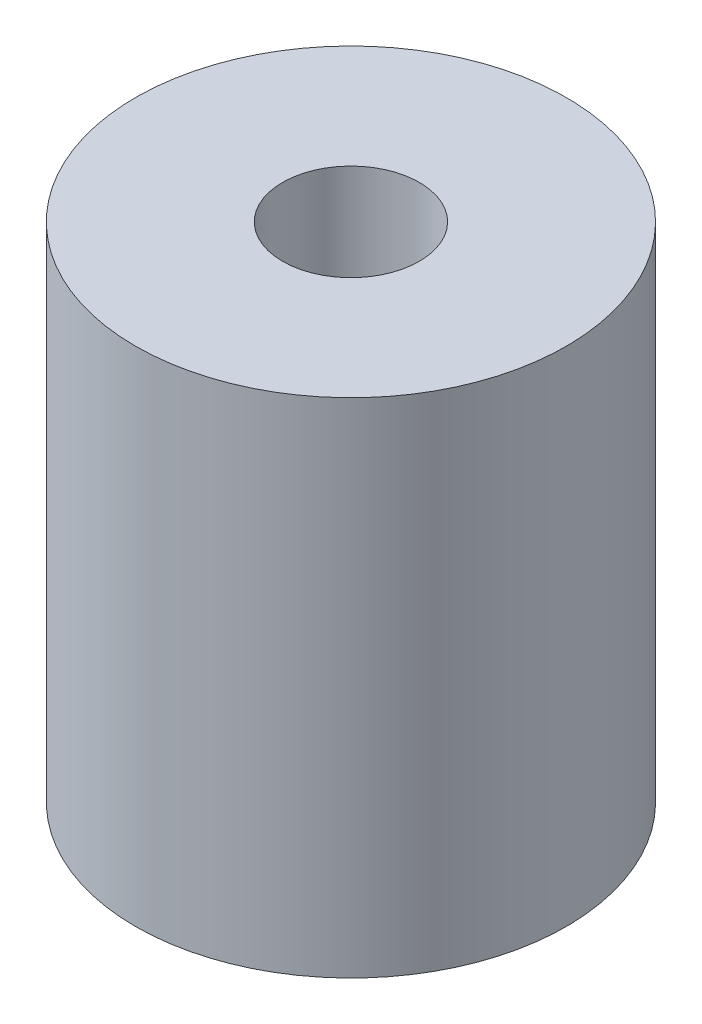
SolidWorks part; units mm, degrees
ref_plane "Front Plane" through (0, 0, 0) normal (0, 0, 1) x (1, 0, 0)
ref_plane "Top Plane" through (0, 0, 0) normal (0, 1, 0) x (1, 0, 0)
ref_plane "Right Plane" through (0, 0, 0) normal (1, 0, 0) x (0, 0, -1)
sketch "Sketch1" plane through (0, 0, 0) normal (0, 1, 0) x (1, 0, 0)
  circle A0 centre (0, 0) radius 15
  dimension "D1" = 30
extrude "Boss-Extrude1" add sketch "Sketch1" along normal blind 35
sketch "Sketch2" plane through (0, 35, 0) normal (0, 1, 0) x (1, 0, 0)
  circle A0 centre (0, 0) radius 4.7625
  dimension "D1" = 9.525
extrude "Cut-Extrude1" cut sketch "Sketch2" against normal blind 11.5
sketch "Sketch3" plane through (0, 0, 0) normal (0, -1, 0) x (1, 0, 0)
  circle A0 centre (0, 0) radius 5
  dimension "D1" = 10
extrude "Cut-Extrude2" cut sketch "Sketch3" against normal blind 11.5
